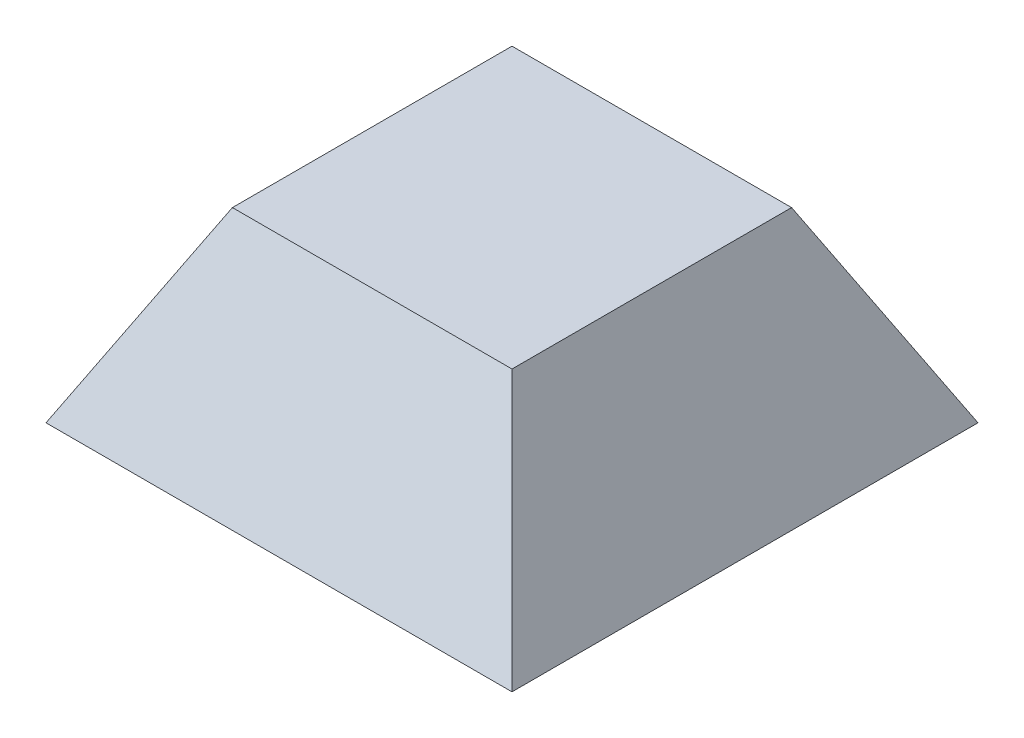
SolidWorks part; units mm, degrees
ref_plane "前视基准面" through (0, 0, 0) normal (0, 0, 1) x (1, 0, 0)
ref_plane "上视基准面" through (0, 0, 0) normal (0, 1, 0) x (1, 0, 0)
ref_plane "右视基准面" through (0, 0, 0) normal (1, 0, 0) x (0, 0, -1)
other "Configuration Table"
sketch "草图1" plane through (0, 0, 0) normal (0, 1, 0) x (1, 0, 0)
  line L1 (-50, -50) -> (50, -50)
  line L2 (-50, -50) -> (-50, 50)
  line L3 (-50, 50) -> (50, 50)
  line L4 (50, -50) -> (50, 50)
  line L5 (-50, -50) -> (50, 50) construction
  line L6 (-50, 50) -> (50, -50) construction
  point P0 (0, 0)
  dimension "D1" = 100
  dimension "D2" = 100
ref_plane "基准面1" through (0, 40, 0) normal (0, 1, 0) x (1, 0, 0)
sketch "草图2" plane through (0, 40, 0) normal (0, 1, 0) x (1, 0, 0)
  line L0 (-50, 50) -> (50, -50) construction
  line L1 (-30, 30) -> (30, 30)
  line L2 (-30, 30) -> (-30, -30)
  line L3 (-30, -30) -> (30, -30)
  line L4 (30, 30) -> (30, -30)
  line L5 (-30, 30) -> (30, -30) construction
  line L6 (-30, -30) -> (30, 30) construction
  point P0 (0, 0)
  dimension "D1" = 60
loft "放样1" add profiles "草图1", "草图2"
